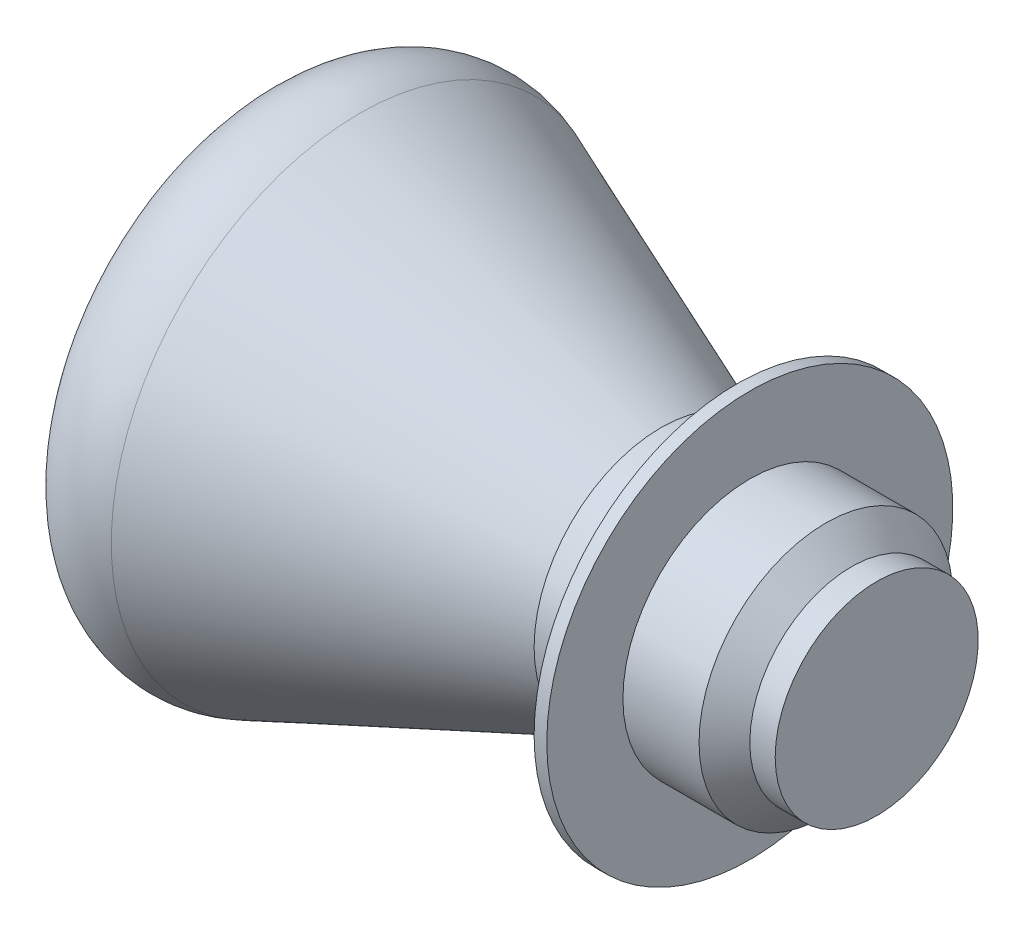
SolidWorks part; units mm, degrees
ref_plane "Front Plane" through (0, 0, 0) normal (0, 0, 1) x (1, 0, 0)
ref_plane "Top Plane" through (0, 0, 0) normal (0, 1, 0) x (1, 0, 0)
ref_plane "Right Plane" through (0, 0, 0) normal (1, 0, 0) x (0, 0, -1)
sketch "Sketch1" plane through (0, 0, 0) normal (0, 0, 1) x (1, 0, 0)
  line L0 (0, 0) -> (5.5, 0)
  line L1 (5.5, 0) -> (5.5, 4)
  line L2 (5.5, 4) -> (4.5, 4)
  line L3 (4.5, 4) -> (3.5, 5)
  line L4 (3.5, 5) -> (0.5, 5)
  line L5 (0.5, 5) -> (0.5, 8)
  line L11 (0, 4.5) -> (0, 0)
  line L12 (0, 4.5) -> (-2, 4.5)
  line L13 (-2, 4.5) -> (-2, 5)
  line L14 (-2, 5) -> (0, 5)
  line L15 (0, 5) -> (0, 8)
  line L16 (0, 8) -> (0.5, 8)
  dimension "D1" = 5.5
  dimension "D2" = 5
  dimension "D3" = 1
  dimension "D4" = 1
  dimension "D5" = 3
  dimension "D6" = 2
  dimension "D7" = 0.5
  dimension "D8" = 3
  dimension "D9" = 0.5
  dimension "D10" = 1
revolve "Revolve1" add sketch "Sketch1" angle 360 about L0
sketch "Sketch2" plane through (0, 0, 0) normal (0, 0, 1) x (1, 0, 0)
  line L4 (0, 0) -> (0, 5)
  line L5 (0, 5) -> (-3, 5)
  line L6 (-3, 5) -> (-14.8796, 9.7829)
  line L7 (0, 0) -> (-19.9983, 0)
  arc A3 (-18.8804, 7.8387) -> (-19.9983, 0) centre (8.0417, 0) ccw
  arc A4 (-14.8796, 9.7829) -> (-18.8804, 7.8387) centre (-16, 7) ccw
  point P2 (0, 0)
  point P4 (0, 0)
  point P5 (0, 0)
  point P13 (0, 0)
  point P14 (0, 0)
  point P15 (0, 0)
  point P16 (0, 0)
  dimension "D1" = 28.04
  dimension "D4" = 16
  dimension "D2" = 3
  dimension "D3" = 2
  dimension "D5" = 3
revolve "Revolve2" add sketch "Sketch2" angle 360 about L7
